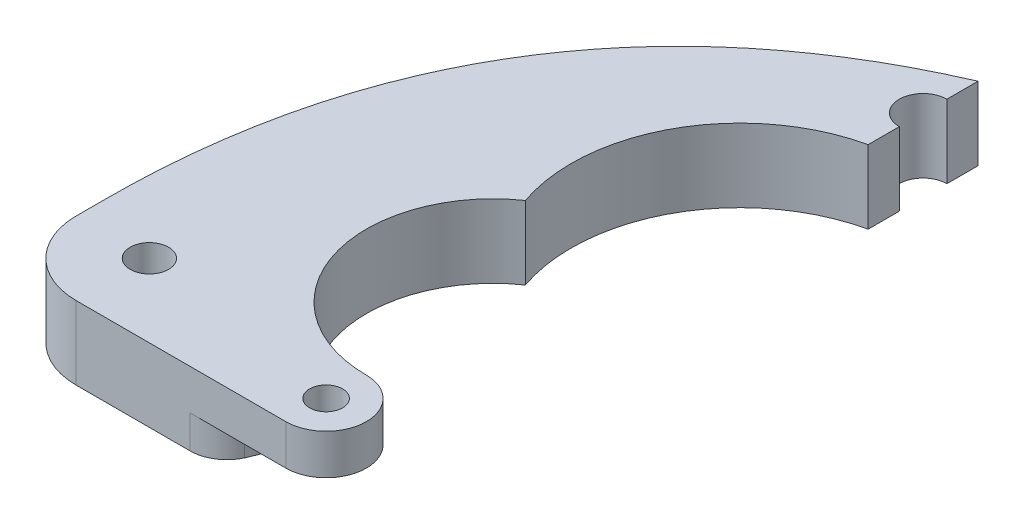
SolidWorks part; units mm, degrees
ref_plane "Front Plane" through (0, 0, 0) normal (0, 0, 1) x (1, 0, 0)
ref_plane "Top Plane" through (0, 0, 0) normal (0, 1, 0) x (1, 0, 0)
ref_plane "Right Plane" through (0, 0, 0) normal (1, 0, 0) x (0, 0, -1)
sketch "Sketch1" plane through (0, 0, 0) normal (0, 1, 0) x (1, 0, 0)
  line L8 (0, 51.3) -> (0, 53)
  line L9 (-18.25, 23.6) -> (-18.25, 22)
  line L10 (-14.25, 18) -> (-2.8, 18)
  line L11 (0, 47) -> (0, 48.7)
  circle A1 centre (-2.8, 20.2) radius 0.9
  circle A3 centre (-14.25, 22) radius 1.05
  arc A10 (0, 51.3) -> (0, 48.7) centre (0, 50) ccw
  arc A11 (-18.25, 22) -> (-14.25, 18) centre (-14.25, 22) ccw
  arc A12 (-2.8, 18) -> (-2.8, 22.4) centre (-2.8, 20.2) ccw
  arc A13 (-6.7178, 35) -> (-2.8, 22.4) centre (-2.8, 29.3091) ccw
  arc A14 (0, 47) -> (-6.7178, 35) centre (2, 38) ccw
  spline S2 degree 3 poles (0, 53) (-11.2886, 48.1071) (-18.25, 38.6913) (-18.25, 23.6) knots 0 0 0 0 1 1 1 1
  dimension "D1" = 1.8
  dimension "D2" = 2.1
  dimension "D3" = 1.3
  dimension "D4" = 4
  dimension "D5" = 2.2
  dimension "D6" = 6.9091
  dimension "D7" = 9.2195
  dimension "D8" = 2
  dimension "D9" = 2.8
  dimension "D10" = 6.7178
  dimension "D11" = 18.25
  dimension "D12" = 18
  dimension "D13" = 50
  dimension "D14" = 23.6
extrude "Boss-Extrude2" add sketch "Sketch1" along normal blind 4 contours L10 A12 A13 A14 L11 A10 L8 S2 L9 A11
sketch "Sketch2" plane through (0, 0, 0) normal (0, -1, 0) x (1, 0, 0)
  line L0 (-14.25, -18) -> (-2.8, -18) construction
  line L1 (-6.9238, -18) -> (-2.8, -18)
  arc A3 (-2.8, -22.4) -> (-6.7178, -35) centre (-2.8, -29.3091) ccw construction
  arc A4 (-2.8, -18) -> (-2.8, -22.4) centre (-2.8, -20.2) cw
  arc A5 (-2.8, -22.4) -> (-5.8, -23.0853) centre (-2.8, -29.3091) ccw
  arc A6 (-6.9238, -18) -> (-5.8, -23.0853) centre (-11.64, -21.7091) cw
  dimension "D1" = 6
  dimension "D2" = 3
extrude "Cut-Extrude1" cut sketch "Sketch2" against normal blind 1.8
fillet "Fillet3" radius 2 2 edges at (-5.8, 0.9, -23.0853) (-6.9238, 0.9, -18)
